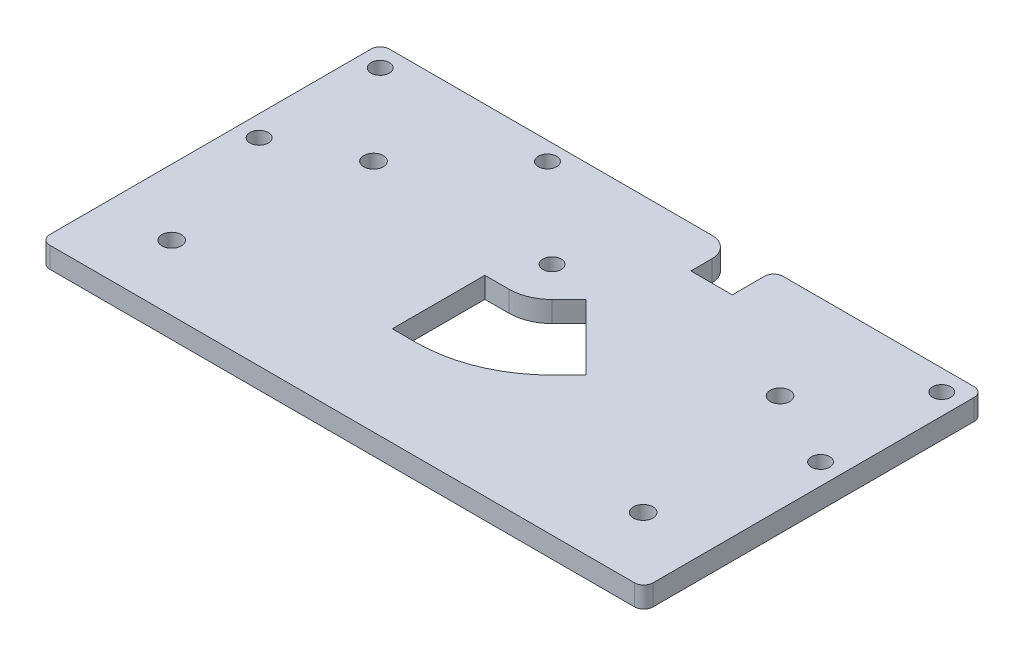
SolidWorks part; units mm, degrees
ref_plane "Front Plane" through (0, 0, 0) normal (0, 0, 1) x (1, 0, 0)
ref_plane "Top Plane" through (0, 0, 0) normal (0, 1, 0) x (1, 0, 0)
ref_plane "Right Plane" through (0, 0, 0) normal (1, 0, 0) x (0, 0, -1)
sketch "Sketch1" plane through (0, 0, 0) normal (0, 1, 0) x (1, 0, 0)
  line L0 (-65, 0) -> (65, 0) construction
  line L1 (63, 20.3) -> (21.8, 20.3)
  line L2 (65, 18.3) -> (65, -50.9)
  line L3 (63, -52.9) -> (-63, -52.9)
  line L4 (-65, 18.3) -> (-65, -50.9)
  line L5 (-65, -14.8) -> (65, -14.8) construction
  line L6 (-65, -46.169) -> (65, -46.169) construction
  line L7 (-50.8, -14.8) -> (-50.8, -46.169) construction
  line L8 (10.87, 15.95) -> (10.87, 11.37)
  line L9 (10.87, 11.37) -> (19.8, 11.37)
  line L10 (19.8, 18.3) -> (19.8, 11.37)
  line L11 (0, 20.3) -> (0, -52.9) construction
  line L12 (6.52, 20.3) -> (-63, 20.3)
  line L13 (-43.8023, -14.8) -> (-43.8023, 20.3) construction
  line L14 (-5.3283, -2.3397) -> (-43.8023, -2.3397) construction
  line L15 (-5.3283, -2.3397) -> (-10.5129, -2.3397) construction
  line L16 (-5.3283, -31.5897) -> (-10.5083, -31.5897)
  line L17 (-10.5114, -11.6297) -> (-10.5083, -31.5897)
  line L18 (-5.3283, -11.6297) -> (-10.5114, -11.6297)
  line L19 (-5.3283, -2.3397) -> (-5.3283, -18.7889) construction
  line L20 (-5.3283, -2.3397) -> (-1.6655, 1.3232) construction
  line L21 (-5.3283, -2.3397) -> (15.3545, -23.0225) construction
  line L22 (-50.8, -29.8387) -> (-45.9526, -29.8387) construction
  line L23 (15.3545, -23.0225) -> (19.0174, -19.3597)
  line L24 (1.2407, -8.9087) -> (4.9035, -5.2459)
  line L25 (4.9035, -5.2459) -> (19.0174, -19.3597)
  circle A0 centre (-60.5, 15.8) radius 1.975
  circle A1 centre (60.5, 15.8) radius 1.975
  circle A2 centre (60.5, -10.3) radius 1.975
  circle A3 centre (-60.5, -10.3) radius 1.975
  circle A4 centre (-25.0043, 16.35) radius 1.975
  arc A5 (10.87, 15.95) -> (6.52, 20.3) centre (6.52, 15.95) ccw
  circle A6 centre (-5.3283, -2.3397) radius 1.975
  arc A7 (63, 20.3) -> (65, 18.3) centre (63, 18.3) cw
  arc A8 (21.8, 20.3) -> (19.8, 18.3) centre (21.8, 18.3) ccw
  arc A9 (-63, 20.3) -> (-65, 18.3) centre (-63, 18.3) ccw
  arc A10 (65, -50.9) -> (63, -52.9) centre (63, -50.9) cw
  arc A11 (-63, -52.9) -> (-65, -50.9) centre (-63, -50.9) cw
  circle A12 centre (-50.8, -38.8387) radius 2.1082
  circle A13 centre (50.8, -38.8387) radius 2.1082
  circle A14 centre (-43.8023, -2.3397) radius 2.1082
  circle A15 centre (43.8023, -2.3397) radius 2.1082
  arc A16 (-5.3283, -31.5897) -> (15.3545, -23.0225) centre (-5.3283, -2.3397) ccw
  arc A17 (-5.3283, -11.6297) -> (1.2407, -8.9087) centre (-5.3283, -2.3397) ccw
  point P0 (0, 0)
  point P26 (10.87, 20.3)
  point P31 (65, 20.3)
  point P36 (-65, 20.3)
  dimension "D6" = 3.95
  dimension "D9" = 3.95
  dimension "D12" = 4.35
  dimension "D13" = 3.95
  dimension "D16" = 3.95
  dimension "D20" = 2
  dimension "D21" = 2
  dimension "D24" = 4.2164
  dimension "D27" = 4.2164
  dimension "D29" = 58.5
  dimension "D32" = 18.58
  dimension "D1" = 130
  dimension "D2" = 30.6
  dimension "D3" = 8.93
  dimension "D4" = 8.93
  dimension "D5" = 45.2
  dimension "D7" = 4.5
  dimension "D8" = 4.5
  dimension "D10" = 35.5
  dimension "D11" = 3.95
  dimension "D14" = 73.2
  dimension "D15" = 4.5
  dimension "D17" = 4.6793
  dimension "D18" = 5.3283
  dimension "D19" = 20.3
  dimension "D22" = 38.1
  dimension "D23" = 31.369
  dimension "D25" = 50.8
  dimension "D26" = 43.8023
  dimension "D28" = 38.474
  dimension "D30" = 5.1845
  dimension "D31" = 5.18
  dimension "D33" = 45
  dimension "D34" = 90
  dimension "D35" = 5.18
  dimension "D36" = 5.18
  dimension "D37" = 5.1831
  dimension "D38" = 5.18
  dimension "D39" = 9
extrude "Boss-Extrude1" add sketch "Sketch1" along normal blind 4.5
